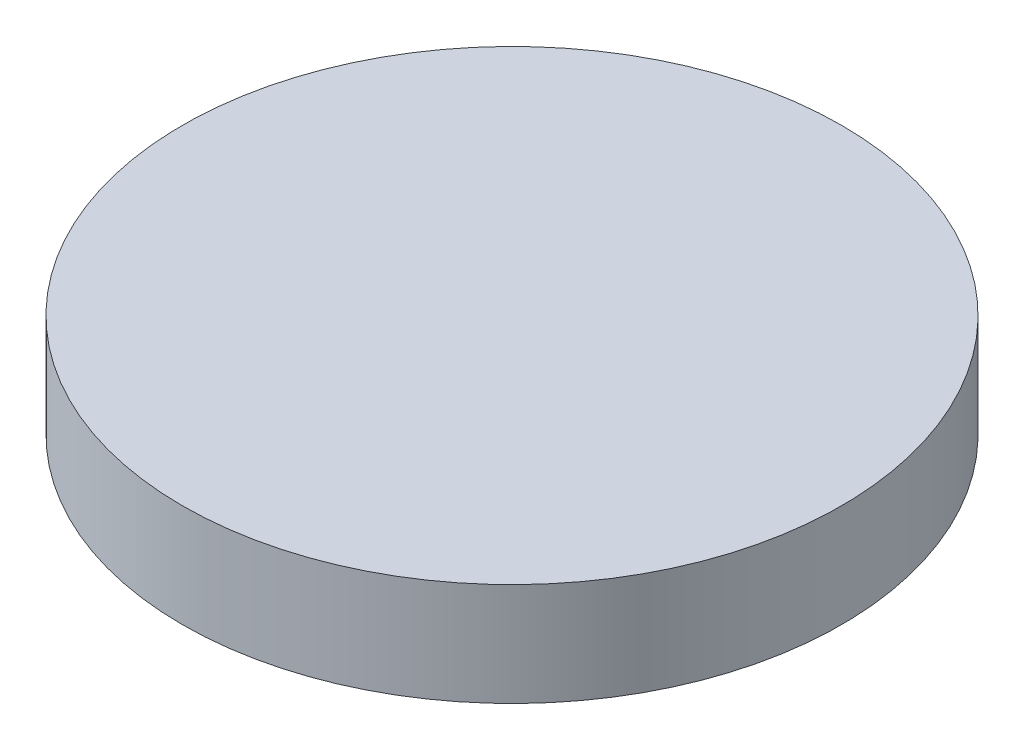
SolidWorks part; units mm, degrees
ref_plane "Front Plane" through (0, 0, 0) normal (0, 0, 1) x (1, 0, 0)
ref_plane "Top Plane" through (0, 0, 0) normal (0, 1, 0) x (1, 0, 0)
ref_plane "Right Plane" through (0, 0, 0) normal (1, 0, 0) x (0, 0, -1)
sketch "Sketch1" plane through (0, 0, 0) normal (0, 1, 0) x (1, 0, 0)
  line L0 (0, -55) -> (0, 55) construction
  line L1 (-55, 0) -> (55, 0) construction
  circle A0 centre (0, 0) radius 10.16
  circle A1 centre (0, 4.953) radius 4.55
  circle A2 centre (0, -4.953) radius 4.55
  circle A3 centre (0, 4.953) radius 3.55
  circle A4 centre (0, -4.953) radius 3.55
  dimension "D1" = 20.32
  dimension "D2" = 9.1
  dimension "D3" = 9.906
  dimension "D4" = 1
extrude "Boss-Extrude1" add sketch "Sketch1" along normal blind 3.175 contours A0 A1 A2 | A1 A3 | A3 | A4 | A2 A4
sketch "Sketch2" plane through (0, 0, 0) normal (0, -1, 0) x (1, 0, 0)
  circle A0 centre (0, -4.953) radius 4.55 construction
  circle A1 centre (0, -4.953) radius 3.55 construction
  circle A2 centre (0, 4.953) radius 4.55 construction
  circle A3 centre (0, 4.953) radius 3.55 construction
  circle A4 centre (0, -4.953) radius 4.55
  circle A5 centre (0, -4.953) radius 3.55
  circle A6 centre (0, 4.953) radius 4.55
  circle A7 centre (0, 4.953) radius 3.55
extrude "Cut-Extrude1" cut sketch "Sketch2" against normal blind 1.524
